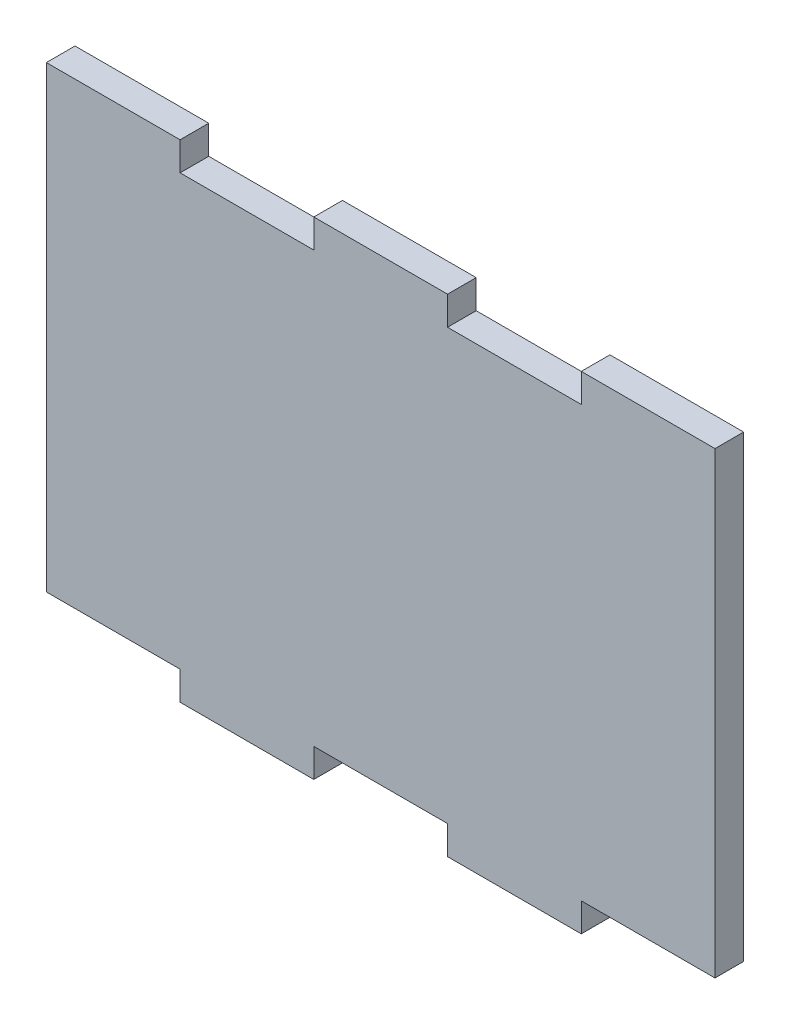
SolidWorks part; units mm, degrees
ref_plane "Front Plane" through (0, 0, 0) normal (0, 0, 1) x (1, 0, 0)
ref_plane "Top Plane" through (0, 0, 0) normal (0, 1, 0) x (1, 0, 0)
ref_plane "Right Plane" through (0, 0, 0) normal (1, 0, 0) x (0, 0, -1)
sketch "Sketch1" plane through (0, 0, 0) normal (0, 0, 1) x (1, 0, 0)
  line L1 (-7, 0) -> (7, 0)
  line L2 (7, 0) -> (7, -3)
  line L3 (-21, -3) -> (-7, -3)
  line L4 (21, -3) -> (21, 0)
  line L5 (21, 0) -> (35, 0)
  line L6 (35, 0) -> (35, 48)
  line L7 (35, 48) -> (21, 48)
  line L8 (21, 48) -> (21, 45)
  line L9 (-21, 45) -> (-7, 45)
  line L10 (7, 45) -> (7, 48)
  line L11 (7, 48) -> (-7, 48)
  line L12 (7, 45) -> (21, 45)
  line L13 (-7, 45) -> (-7, 48)
  line L14 (-21, 48) -> (-21, 45)
  line L15 (-35, 48) -> (-21, 48)
  line L16 (-35, 0) -> (-35, 48)
  line L17 (-21, 0) -> (-35, 0)
  line L18 (-21, -3) -> (-21, 0)
  line L19 (7, -3) -> (21, -3)
  line L20 (-7, 0) -> (-7, -3)
  dimension "D2" = 14
  dimension "D3" = 14
  dimension "D4" = 48
  dimension "D5" = 14
  dimension "D6" = 14
  dimension "D7" = 48
  dimension "D8" = 3
  dimension "D9" = 14
  dimension "D10" = 3
  dimension "D11" = 3
  dimension "D12" = 14
extrude "Boss-Extrude1" add sketch "Sketch1" along normal blind 3
